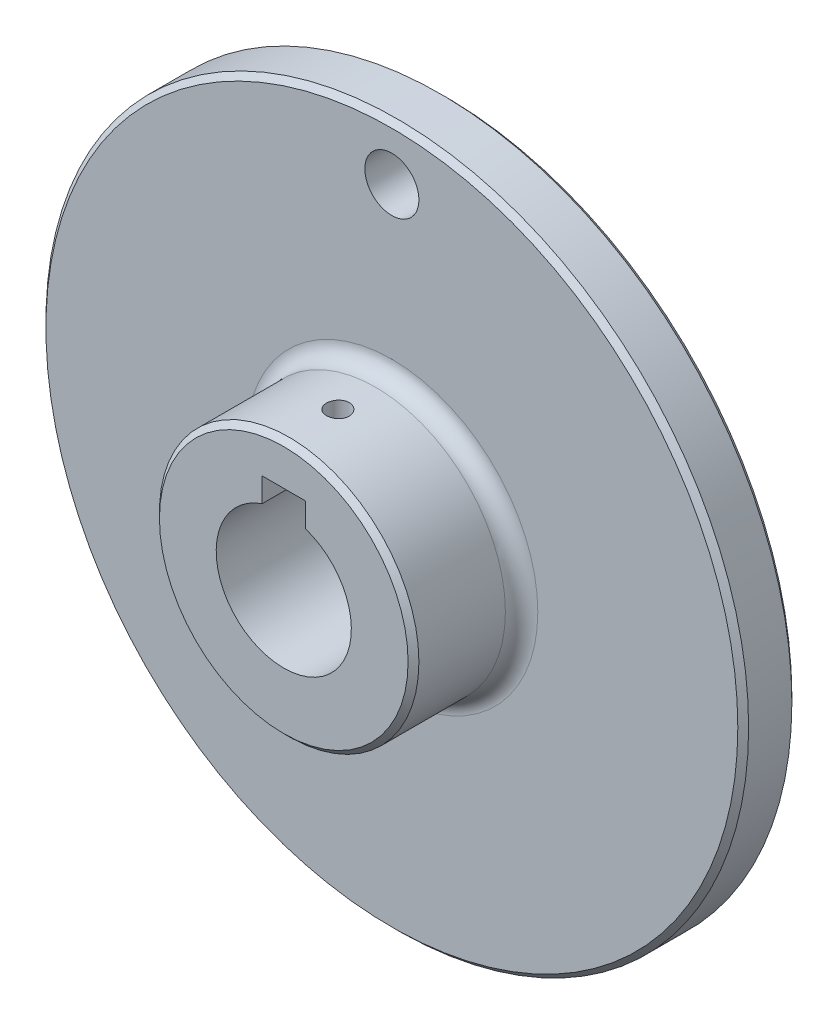
SolidWorks part; units mm, degrees
ref_plane "Plano frontal" through (0, 0, 0) normal (0, 0, 1) x (1, 0, 0)
ref_plane "Plano superior" through (0, 0, 0) normal (0, 1, 0) x (1, 0, 0)
ref_plane "Plano direito" through (0, 0, 0) normal (1, 0, 0) x (0, 0, -1)
sketch "Sketch1" plane through (0, 0, 0) normal (0, 0, 1) x (1, 0, 0)
  line L0 (0, 0) -> (0, 55) construction
  circle A0 centre (0, 0) radius 65
  circle A1 centre (0, 55) radius 5
  circle A2 centre (0, 0) radius 12.5
  dimension "D1" = 130
  dimension "D2" = 10
  dimension "D4" = 25
  dimension "D3" = 55
extrude "Boss-Extrude1" add sketch "Sketch1" along normal blind 10
sketch "Sketch2" plane through (0, 0, 10) normal (0, 0, 1) x (1, 0, 0)
  circle A0 centre (0, 0) radius 12.5
  circle A1 centre (0, 0) radius 24
  dimension "D1" = 25
  dimension "D2" = 48
extrude "Boss-Extrude2" add sketch "Sketch2" along normal blind 20
chamfer "Chamfer1" distance 1 angle 45 2 edges at (65, 0, 0) (65, 0, 10)
fillet "Fillet1" radius 3 1 edges at (24, 0, 10)
chamfer "Chamfer2" distance 1 angle 45 1 edges at (24, 0, 30)
sketch "Sketch4" plane through (0, 0, 30) normal (0, 0, 1) x (1, 0, 0)
  line L1 (-4, 0) -> (4, 0)
  line L2 (-4, 0) -> (-4, 16.3)
  line L3 (-4, 16.3) -> (4, 16.3)
  line L4 (4, 0) -> (4, 16.3)
  line L5 (0, 16.3) -> (0, 0) construction
  line L6 (-4, 8.15) -> (4, 8.15) construction
  point P180 (0, 8.15)
  dimension "D1" = 16.3
  dimension "D2" = 8
extrude "Cut-Extrude2" cut sketch "Sketch4" against normal through all
hole_wizard "M5 Tapped Hole1" positions "Sketch6" profile "Sketch5" tap size "M5" standard "DIN"
sketch "Sketch6" plane through (0, 16.3, 0) normal (0, -1, 0) x (-1, 0, 0)
  line L0 (0, 0) -> (0, -20) construction
  line L2 (-4, -30) -> (4, -30) construction
  point P0 (0, -20)
  dimension "D1" = 10
sketch "Sketch5" plane through (0, 16.3, 20) normal (1, 0, 0) x (0, 0, -1)
  line L0 (0, 0) -> (0, 13.6618)
  line L1 (0, 13.6618) -> (2.1, 12.4)
  line L2 (2.1, 12.4) -> (2.1, 0)
  line L5 (2.1, 0) -> (0, 0)
  line L10 (0, 13.6618) -> (-2.1, 12.4) construction
  line L11 (0, -6.35) -> (0, 107.95) construction
  dimension "Tap Drill Dia." = 4.2
  dimension "Tap Drill Depth" = 12.4
  dimension "Drill Angle" = 118
cosmetic thread "Hole Thread1" parameters "D1"=6.2, "D2"=5
ref_point "Point3"
ref_point "Point4"
